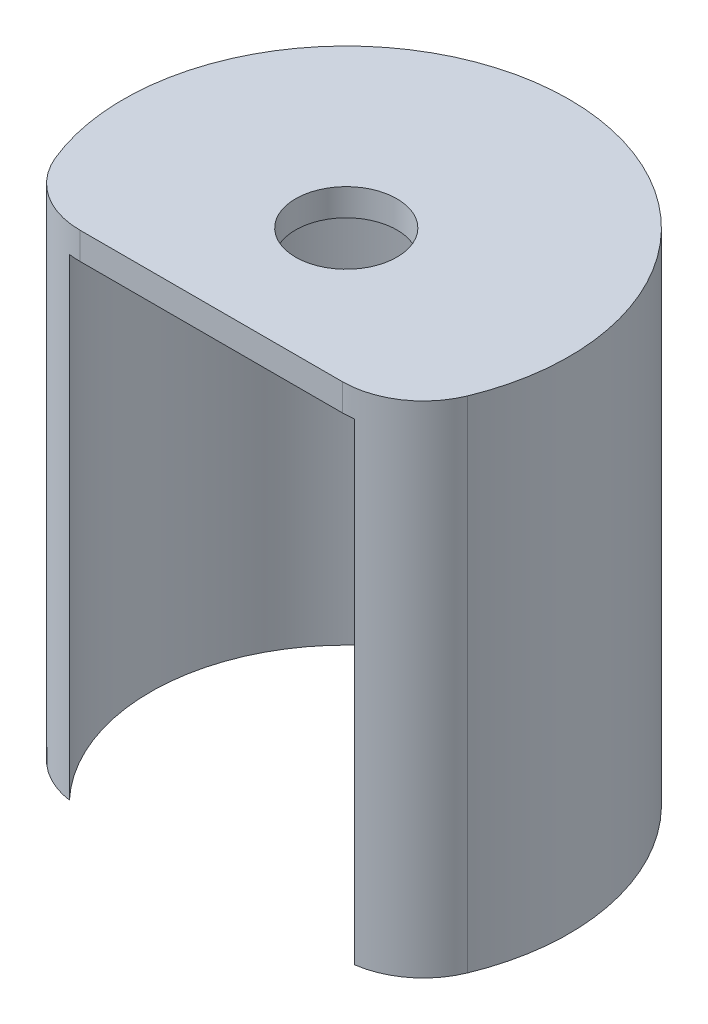
SolidWorks part; units mm, degrees
ref_plane "前视基准面" through (0, 0, 0) normal (0, 0, 1) x (1, 0, 0)
ref_plane "上视基准面" through (0, 0, 0) normal (0, 1, 0) x (1, 0, 0)
ref_plane "右视基准面" through (0, 0, 0) normal (1, 0, 0) x (0, 0, -1)
other "Configuration Table"
sketch "草图1" plane through (0, 0, 0) normal (0, 1, 0) x (1, 0, 0)
  circle A0 centre (0, 0) radius 14.5
  circle A1 centre (0, 0) radius 16.5
  dimension "D1" = 29
  dimension "D2" = 2
extrude "凸台-拉伸1" add sketch "草图1" along normal blind 35
sketch "草图3" plane through (0, 35, 0) normal (0, 1, 0) x (1, 0, 0)
  circle A1 centre (0, 0) radius 16.5
  circle A2 centre (0, 0) radius 16.5
  dimension "D1" = 0
extrude "凸台-拉伸2" add sketch "草图3" along normal blind 2
ref_plane "基准面1" through (0, 0, 10) normal (0, 0, 1) x (1, 0, 0)
sketch "草图4" plane through (0, 0, 10) normal (0, 0, 1) x (1, 0, 0)
  line L1 (-21.3332, 39.7218) -> (28.4145, 39.7218)
  line L2 (-21.3332, 39.7218) -> (-21.3332, -3.9689)
  line L3 (-21.3332, -3.9689) -> (28.4145, -3.9689)
  line L4 (28.4145, 39.7218) -> (28.4145, -3.9689)
extrude "切除-拉伸1" cut sketch "草图4" along normal through all
sketch "草图5" plane through (0, 37, 0) normal (0, 1, 0) x (1, 0, 0)
  circle A0 centre (0, 0) radius 3.75
  dimension "D1" = 7.5
extrude "切除-拉伸2" cut sketch "草图5" against normal up to next
fillet "圆角1" radius 6 2 edges at (13.1244, 18.5, 10) (-13.1244, 18.5, 10)
